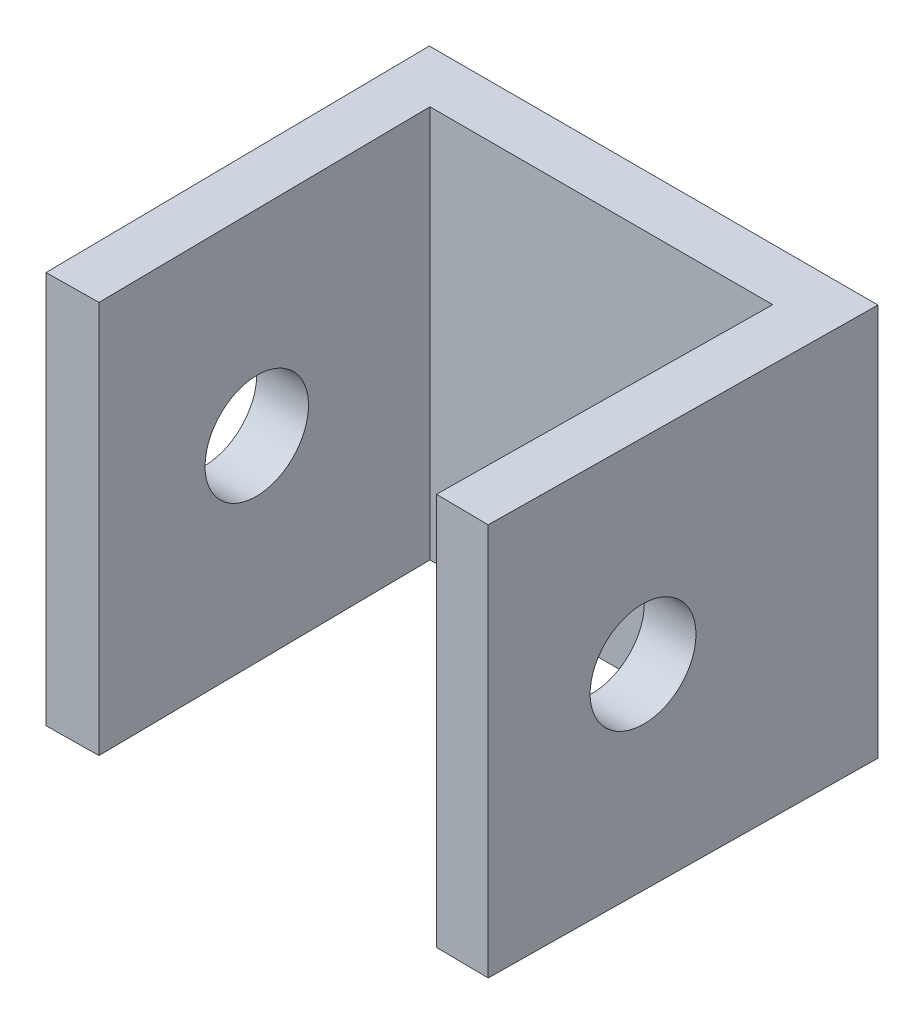
SolidWorks part; units mm, degrees
ref_plane "Front Plane" through (0, 0, 0) normal (0, 0, 1) x (1, 0, 0)
ref_plane "Top Plane" through (0, 0, 0) normal (0, 1, 0) x (1, 0, 0)
ref_plane "Right Plane" through (0, 0, 0) normal (1, 0, 0) x (0, 0, -1)
sketch "Sketch1" plane through (0, 0, 0) normal (0, 1, 0) x (1, 0, 0)
  line L0 (-12.8, -12.8) -> (-13.1, 12.8)
  line L1 (-12.8, 12.8) -> (12.8, 12.8) construction
  line L2 (-12.8, 12.8) -> (-12.8, -12.8) construction
  line L4 (12.8, 12.8) -> (12.8, -12.6) construction
  line L5 (-13.1, 12.8) -> (13.1, 12.8)
  line L6 (13.1, 12.8) -> (12.8, -12.6)
  line L7 (-16.7997, -12.8469) -> (-17.1471, 16.8)
  line L8 (-17.1471, 16.8) -> (17.1475, 16.8)
  line L9 (17.1475, 16.8) -> (16.7997, -12.6472)
  line L11 (-16.7997, -12.8469) -> (-12.8, -12.8)
  line L12 (12.8, -12.6) -> (16.7997, -12.6472)
  dimension "D1" = 25.6
  dimension "D2" = 25.4
  dimension "D3" = 0.3
  dimension "D4" = 0.3
  dimension "D5" = 4
extrude "Boss-Extrude1" add sketch "Sketch1" along normal blind 30
sketch "Sketch2" plane through (0, 30, 0) normal (0, 1, 0) x (1, 0, 0)
  line L0 (0.0002, 16.8) -> (0.0002, 30.8112) construction
  line L1 (17.1475, 16.8) -> (-17.1471, 16.8) construction
  line L2 (0.0002, 36.8) -> (-4.0998, 36.8) construction
  line L3 (0.0002, 36.8) -> (2.1002, 36.8) construction
  line L4 (-4.0998, 36.8) -> (-4.0998, 23.7851)
  line L5 (-2.0998, 36.8) -> (-2.0998, 23.7851)
  line L6 (-11.0849, 16.8) -> (-5.4334, 16.8)
  line L7 (-4.0998, 36.8) -> (-2.0998, 36.8)
  line L8 (4.1002, 36.8) -> (2.1002, 36.8)
  line L9 (11.0853, 16.8) -> (5.4337, 16.8)
  line L10 (2.1002, 36.8) -> (2.1002, 23.7851)
  line L11 (4.1002, 36.8) -> (4.1002, 23.7851)
  arc A0 (-4.0998, 23.7851) -> (-11.0849, 16.8) centre (-11.0849, 23.7851) cw
  arc A1 (-2.0998, 23.7851) -> (-5.4334, 16.8) centre (-11.0849, 23.7851) cw
  arc A2 (-2.0998, 23.7851) -> (-11.0849, 14.8) centre (-11.0849, 23.7851) cw construction
  arc A3 (4.1002, 23.7851) -> (11.0853, 16.8) centre (11.0853, 23.7851) ccw
  arc A4 (2.1002, 23.7851) -> (5.4337, 16.8) centre (11.0853, 23.7851) ccw
  dimension "D1" = 20
  dimension "D2" = 4.1
  dimension "D3" = 2
sketch "Sketch3" plane through (16.9467, 0, 0.2002) normal (0.9999, 0, 0.0118) x (0.0118, 0, -0.9999)
  line L0 (-12.448, 0) -> (10.952, 0) construction
  line L1 (-0.748, 0) -> (-0.748, 30) construction
  line L5 (-12.448, 30) -> (17.0013, 30) construction
  circle A0 centre (-0.748, 15) radius 4
  dimension "D1" = 11.7
extrude "Cut-Extrude1" cut sketch "Sketch3" against normal blind 40
sketch "Sketch4" plane through (0, 0, -16.8) normal (0, 0, -1) x (-1, 0, 0)
  line L0 (17.1471, 0) -> (-17.1475, 30) construction
  line L1 (-0.0002, 15) -> (10.9998, 15) construction
  line L2 (10.9998, -5.5) -> (10.9998, 35.5)
  line L3 (10.9998, 35.5) -> (13.9998, 35.5)
  line L4 (10.9998, -5.5) -> (13.9998, -5.5)
  line L6 (13.9998, 35.5) -> (13.9998, -5.5)
  point P8 (10.9998, 15)
  dimension "D1" = 3
extrude "Boss-Extrude2" add sketch "Sketch4" against normal blind 4
sketch "Sketch5" plane through (0, 0, -16.8) normal (0, 0, -1) x (-1, 0, 0)
  line L1 (13.9998, 35.5) -> (13.9998, 43.25)
  line L11 (10.9998, 35.5) -> (10.9998, 43.25)
  line L17 (10.9998, 35.5) -> (13.9998, 35.5)
  line L18 (10.9998, 43.25) -> (13.9998, 43.25)
  line L21 (17.1471, 15) -> (-23.8791, 15) construction
  line L22 (17.1471, 30) -> (17.1471, 0) construction
  line L23 (10.9998, -13.25) -> (13.9998, -13.25)
  line L24 (10.9998, -5.5) -> (13.9998, -5.5)
  line L25 (10.9998, -5.5) -> (10.9998, -13.25)
  line L26 (13.9998, -5.5) -> (13.9998, -13.25)
extrude "Boss-Extrude3" add sketch "Sketch5" against normal blind 4 and the other way blind 25
sketch "Sketch6" plane through (-13.9998, 0, 0) normal (-1, 0, 0) x (0, 0, 1)
  line L0 (-16.8, 43.25) -> (-16.8, -13.25)
  line L1 (-41.8, 43.25) -> (-12.8, 43.25) construction
  line L2 (-12.8, -13.25) -> (-12.8, 43.25)
  line L3 (-12.8, -13.25) -> (-16.8, -13.25)
  line L4 (-12.8, 43.25) -> (-16.8, 43.25)
extrude "Boss-Extrude4" add sketch "Sketch6" along normal up to surface (3.1005 mm away)
sketch "Sketch7" plane through (-16.9479, 0, 0.1986) normal (-0.9999, 0, 0.0117) x (0.0117, 0, 0.9999)
  line L0 (12.6491, 30) -> (-40.2558, 30)
  line L1 (-40.2558, 30) -> (-53.5662, 38.8911)
  line L2 (-53.5662, 38.8911) -> (-52.1927, 50.0279)
  line L3 (-52.1927, 50.0279) -> (-13.8033, 48.7791)
  line L4 (-13.8033, 48.7791) -> (23.5061, 46.0536)
  line L5 (23.5061, 46.0536) -> (14.6716, 30)
  line L6 (14.6716, 30) -> (12.6491, 30)
  line L7 (12.6491, 0) -> (-49.961, 0)
  line L8 (-49.961, 0) -> (-43.2107, -24.3317)
  line L9 (-43.2107, -24.3317) -> (11.6534, -25.8063)
  line L10 (11.6534, -25.8063) -> (35.291, -15.9344)
  line L11 (35.291, -15.9344) -> (29.6892, -2.5212)
  line L12 (29.6892, -2.5212) -> (12.6491, 0)
extrude "Cut-Extrude2" cut sketch "Sketch7" against normal blind 62
